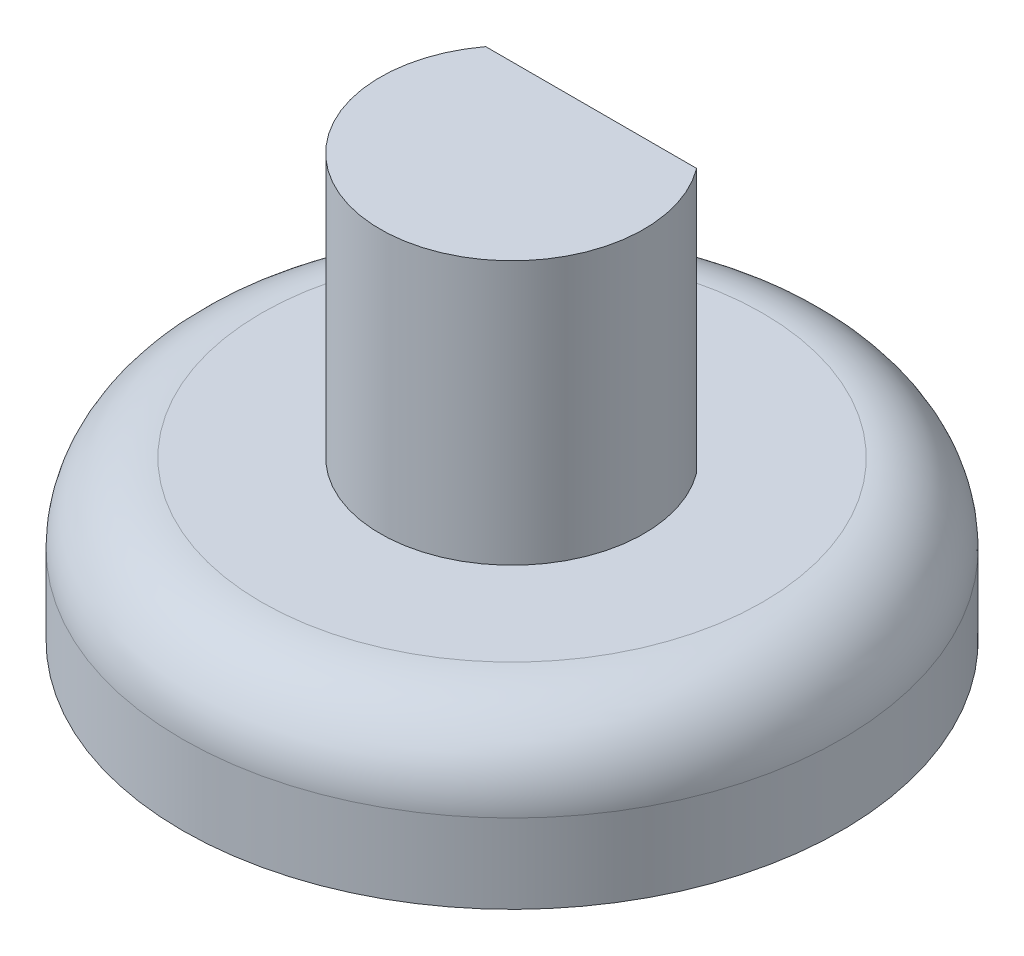
SolidWorks part; units mm, degrees
ref_plane "Front Plane" through (0, 0, 0) normal (0, 0, 1) x (1, 0, 0)
ref_plane "Top Plane" through (0, 0, 0) normal (0, 1, 0) x (1, 0, 0)
ref_plane "Right Plane" through (0, 0, 0) normal (1, 0, 0) x (0, 0, -1)
sketch "Sketch1" plane through (0, 0, 0) normal (0, 1, 0) x (1, 0, 0)
  circle A0 centre (0, 0) radius 6.25
  dimension "D1" = 12.5
extrude "Boss-Extrude1" add sketch "Sketch1" along normal blind 3
sketch "Sketch2" plane through (0, 3, 0) normal (0, 1, 0) x (1, 0, 0)
  line L0 (0, 0) -> (0, 1.5) construction
  line L1 (-2, 1.5) -> (2, 1.5)
  arc A0 (-2, 1.5) -> (2, 1.5) centre (0, 0) ccw
  dimension "D1" = 5
  dimension "D2" = 1.5
extrude "Boss-Extrude2" add sketch "Sketch2" along normal blind 5
fillet "Fillet1" radius 1.5 1 edges at (0, 3, 6.25)
